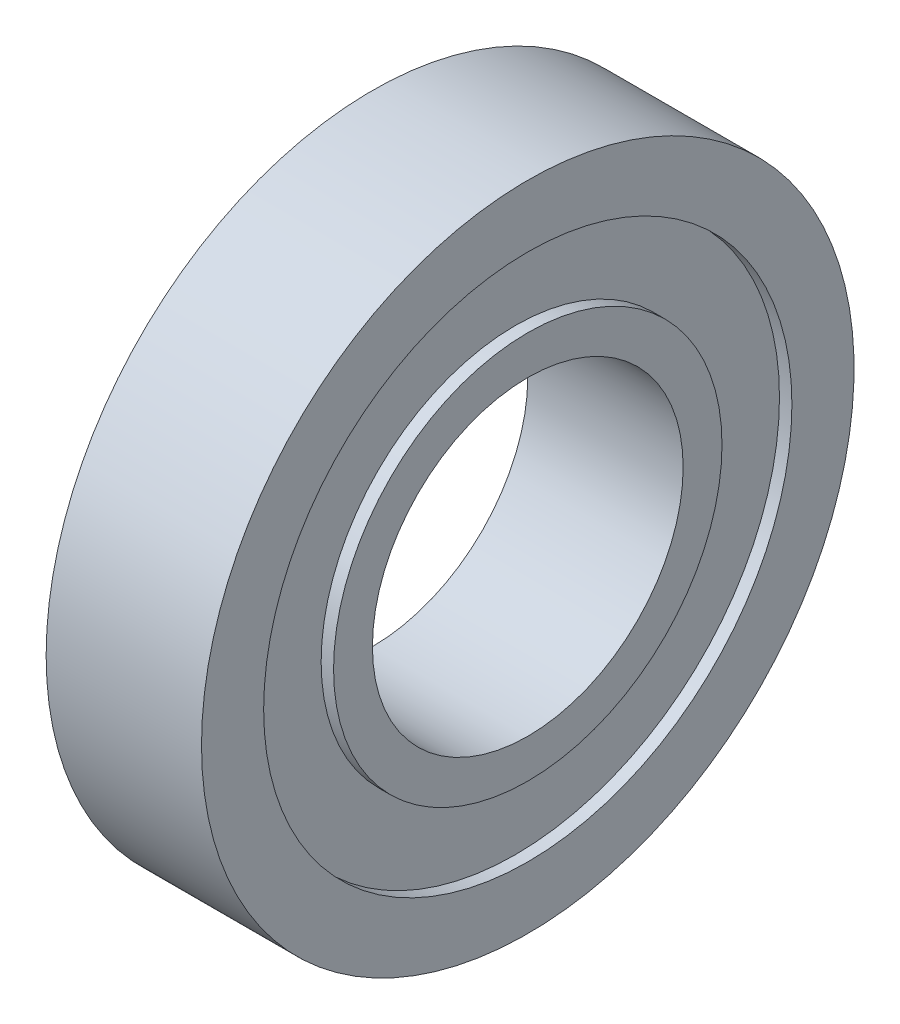
SolidWorks part; units mm, degrees
ref_plane "Front Plane" through (0, 0, 0) normal (0, 0, 1) x (1, 0, 0)
ref_plane "Top Plane" through (0, 0, 0) normal (0, 1, 0) x (1, 0, 0)
ref_plane "Right Plane" through (0, 0, 0) normal (1, 0, 0) x (0, 0, -1)
sketch "Sketch1" plane through (0, 0, 0) normal (0, 1, 0) x (1, 0, 0)
  line L0 (0, 5) -> (0, 6.25)
  line L1 (0, 6.25) -> (0.4, 6.25)
  line L2 (0.4, 6.25) -> (0.4, 8.5)
  line L3 (0.4, 8.5) -> (0, 8.5)
  line L4 (0, 8.5) -> (0, 10.5)
  line L5 (0, 10.5) -> (5, 10.5)
  line L6 (5, 10.5) -> (5, 8.5)
  line L7 (5, 8.5) -> (4.6, 8.5)
  line L8 (4.6, 8.5) -> (4.6, 6.25)
  line L9 (4.6, 6.25) -> (5, 6.25)
  line L10 (5, 6.25) -> (5, 5)
  line L11 (5, 5) -> (0, 5)
  line L12 (0, 0) -> (6.9499, 0) construction
  dimension "D1" = 5
  dimension "D2" = 10.5
  dimension "D3" = 8.5
  dimension "D4" = 6.25
  dimension "D5" = 5
  dimension "D6" = 0.4
revolve "Revolve1" add sketch "Sketch1" angle 360 about L12
